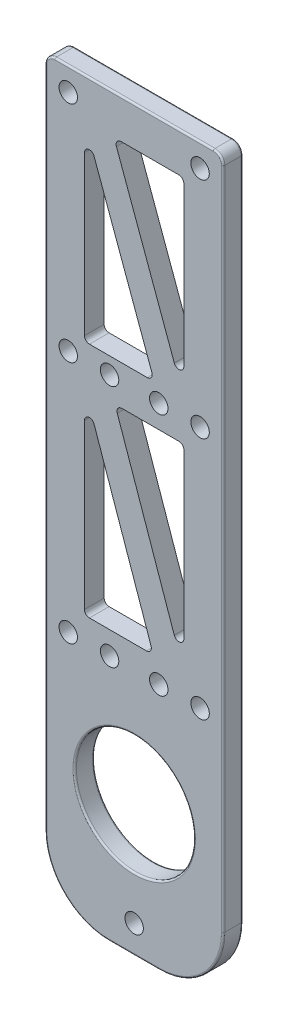
SolidWorks part; units mm, degrees
ref_plane "Front Plane" through (0, 0, 0) normal (0, 0, 1) x (1, 0, 0)
ref_plane "Top Plane" through (0, 0, 0) normal (0, 1, 0) x (1, 0, 0)
ref_plane "Right Plane" through (0, 0, 0) normal (1, 0, 0) x (0, 0, -1)
sketch "Sketch1" plane through (0, 0, 0) normal (0, 0, 1) x (1, 0, 0)
  line L0 (-10.1, 28.1) -> (4.1, 28.1)
  line L1 (-10.1, -20.1) -> (10.1, -20.1)
  line L2 (-10.1, -20.1) -> (-10.1, 20.1)
  line L3 (-10.1, 20.1) -> (10.1, 20.1)
  line L4 (10.1, -20.1) -> (10.1, 20.1)
  line L5 (-10.1, -20.1) -> (10.1, 20.1) construction
  line L6 (-10.1, 20.1) -> (10.1, -20.1) construction
  line L8 (-18.1, -62) -> (-18.1, 75)
  line L9 (-18.1, 75) -> (18.1, 75)
  line L10 (18.1, -62) -> (18.1, 75)
  line L11 (-18.1, -75) -> (18.1, 75) construction
  line L12 (-18.1, 75) -> (18.1, -75) construction
  line L13 (4.1, 28.1) -> (-10.1, 67)
  line L14 (-10.1, 67) -> (-10.1, 28.1)
  line L15 (-5.1, -75) -> (5.1, -75)
  line L17 (10.1, 67) -> (-4.1, 67)
  line L18 (-4.1, 67) -> (10.1, 28.1)
  line L19 (10.1, 28.1) -> (10.1, 67)
  circle A0 centre (0, -48.3) radius 12.1
  arc A1 (-18.1, -62) -> (-5.1, -75) centre (-5.1, -62) ccw
  arc A2 (18.1, -62) -> (5.1, -75) centre (5.1, -62) cw
  point P0 (0, 0)
  point P6 (0, 0)
  dimension "D4" = 24.2
  dimension "D6" = 13
  dimension "D1" = 40.2
  dimension "D2" = 20.2
  dimension "D3" = 150
  dimension "D5" = 28.2
  dimension "D7" = 8
  dimension "D8" = 8
  dimension "D9" = 8
  dimension "D10" = 8
  dimension "D11" = 8
  dimension "D12" = 8
  dimension "D13" = 14.2
  dimension "D14" = 14.2
extrude "Base Plate" add sketch "Sketch1" along normal blind 4
fillet "Fillet1" radius 1 6 edges at (-4.1, 67, 2) (10.1, 67, 2) (-10.1, 67, 2) (-10.1, 28.1, 2) (4.1, 28.1, 2) (10.1, 28.1, 2)
fillet "Fillet2" radius 2 2 edges at (-18.1, 75, 2) (18.1, 75, 2)
sketch "Sketch2" plane through (0, 0, 4) normal (0, 0, 1) x (1, 0, 0)
  line L1 (2.2, 0) -> (-2.2, 0) construction
  line L2 (18.1, -62) -> (18.1, 73) construction
  line L3 (0, -2.2) -> (0, 2.2) construction
  line L4 (0, 75) -> (0, 67) construction
  line L5 (16.1, 75) -> (-16.1, 75) construction
  line L6 (9.1, 67) -> (-2.6704, 67) construction
  line L7 (-5.1, -75) -> (5.1, -75) construction
  circle A0 centre (5, 24.75) radius 1.875
  circle A1 centre (-5, 24.75) radius 1.875
  circle A2 centre (-5, -24.75) radius 1.875
  circle A3 centre (5, -24.75) radius 1.875
  circle A4 centre (13.4, 24.75) radius 1.875
  circle A5 centre (-13.4, 24.75) radius 1.875
  circle A6 centre (13.4, -24.75) radius 1.875
  circle A7 centre (-13.4, -24.75) radius 1.875
  circle A9 centre (13.4, 70.3) radius 1.875
  circle A10 centre (-13.4, 70.3) radius 1.875
  circle A11 centre (0, -69.3) radius 1.875
  dimension "D1" = 3.75
  dimension "D2" = 3.75
  dimension "D6" = 3.75
  dimension "D8" = 3.75
  dimension "D7" = 3.75
  dimension "D3" = 10
  dimension "D4" = 5
  dimension "D5" = 49.5
  dimension "D9" = 4.7
  dimension "D10" = 4.7
  dimension "D11" = 5.7
extrude "Cut-Extrude1" cut sketch "Sketch2" against normal through all
sketch "Sketch3" plane through (10.1, 0, 0) normal (-1, 0, 0) x (0, 0, 1)
  line L4 (0, 20.1) -> (0, -20.1)
  line L5 (0, -20.1) -> (4, -20.1)
  line L6 (4, -20.1) -> (4, 20.1)
  line L7 (4, 20.1) -> (0, 20.1)
  line L8 (0, 20.1) -> (0, -20.1)
  line L9 (0, -20.1) -> (4, -20.1)
  line L10 (4, -20.1) -> (4, 20.1)
  line L11 (4, 20.1) -> (0, 20.1)
  dimension "D1" = 0
extrude "Boss-Extrude1" add sketch "Sketch3" along direction (1, 0, 0) on the side of the normal through all
sketch "Sketch4" plane through (0, 0, 4) normal (0, 0, 1) x (1, 0, 0)
  line L0 (-10.1, 20.1) -> (-10.1, -20.1)
  line L1 (-10.1, -20.1) -> (3.9, -20.1)
  line L2 (3.9, -20.1) -> (-10.1, 20.1)
  line L3 (-3.9, 20.1) -> (10.1, 20.1)
  line L4 (10.1, 20.1) -> (10.1, -20.1)
  line L5 (10.1, -20.1) -> (-3.9, 20.1)
  line L6 (-10.1, 61.3443) -> (-10.1, 29.1) construction
  line L7 (10.1, 33.7557) -> (10.1, 66) construction
  point P13 (10.1, 0)
  dimension "D1" = 14
  dimension "D2" = 14
  dimension "D3" = 40.2
extrude "Cut-Extrude2" cut sketch "Sketch4" against normal through all
fillet "Fillet3" radius 1 6 edges at (10.1, -20.1, 2) (10.1, 20.1, 2) (-3.9, 20.1, 2) (-10.1, 20.1, 2) (3.9, -20.1, 2) (-10.1, -20.1, 2)
sketch "Sketch5" [suppressed] plane through (0, 0, 4) normal (0, 0, 1) x (1, 0, 0)
  line L1 (-10.1, -20.1) -> (10.1, -20.1) construction
  line L2 (0, -20.1) -> (3.25, -20.1) construction
  line L4 (3.25, -20.1) -> (-3.25, -20.1)
  line L5 (3.25, -20.1) -> (3.25, -27.4)
  line L6 (3.25, -27.4) -> (-3.25, -27.4)
  line L7 (-3.25, -20.1) -> (-3.25, -27.4)
  dimension "D2" = 3.25
  dimension "D3" = 6.5
  dimension "D4" = 7.3
extrude "Cut-Extrude3" [suppressed] cut sketch "Sketch5" against normal through all
fillet "Fillet5" radius 0.35 18 edges at (-17.5142, 74.4142, 4) (0, 75, 4) (17.5142, 74.4142, 4) (18.1, 5.5, 4) (14.2924, -71.1924, 4) (0, -75, 4) (-14.2924, -71.1924, 4) (-18.1, 5.5, 0) (-17.5142, 74.4142, 0) (0, 75, 0) (17.5142, 74.4142, 0) (18.1, 5.5, 0) (14.2924, -71.1924, 0) (0, -75, 0) (-18.1, 5.5, 4) (-14.2924, -71.1924, 0) (12.1, -48.3, 0) (12.1, -48.3, 4)
sketch "Sketch6" [suppressed] plane through (0, 0, 4) normal (0, 0, 1) x (1, 0, 0)
  line L1 (-10.375, -20.375) -> (10.375, -20.375)
  line L2 (-10.375, -20.375) -> (-10.375, 20.375)
  line L3 (-10.375, 20.375) -> (10.375, 20.375)
  line L4 (10.375, -20.375) -> (10.375, 20.375)
  line L5 (-10.375, -20.375) -> (10.375, 20.375) construction
  line L6 (-10.375, 20.375) -> (10.375, -20.375) construction
  point P0 (0, 0)
  dimension "D1" = 40.75
  dimension "D2" = 20.75
extrude "Cut-Extrude4" [suppressed] cut sketch "Sketch6" against normal through all
fillet "Fillet4" [suppressed] radius 1
equation "\"D10@Sketch1\"=\"D9@Sketch1\""
equation "\"D11@Sketch1\"=\"D9@Sketch1\""
equation "\"D12@Sketch1\"=\"D9@Sketch1\""
equation "\"D13@Sketch1\"=\"D2@Sketch1\"-6"
equation "\"D14@Sketch1\"=\"D13@Sketch1\""
equation "\"D2@Sketch2\"=\"D1@Sketch2\""
equation "\"D4@Sketch2\"=\"D3@Sketch2\"/2"
equation "\"D9@Sketch2\"=4.7"
equation "\"D10@Sketch2\"=\"D9@Sketch2\""
equation "\"D2@Sketch5\"=\"D3@Sketch5\"/2"
